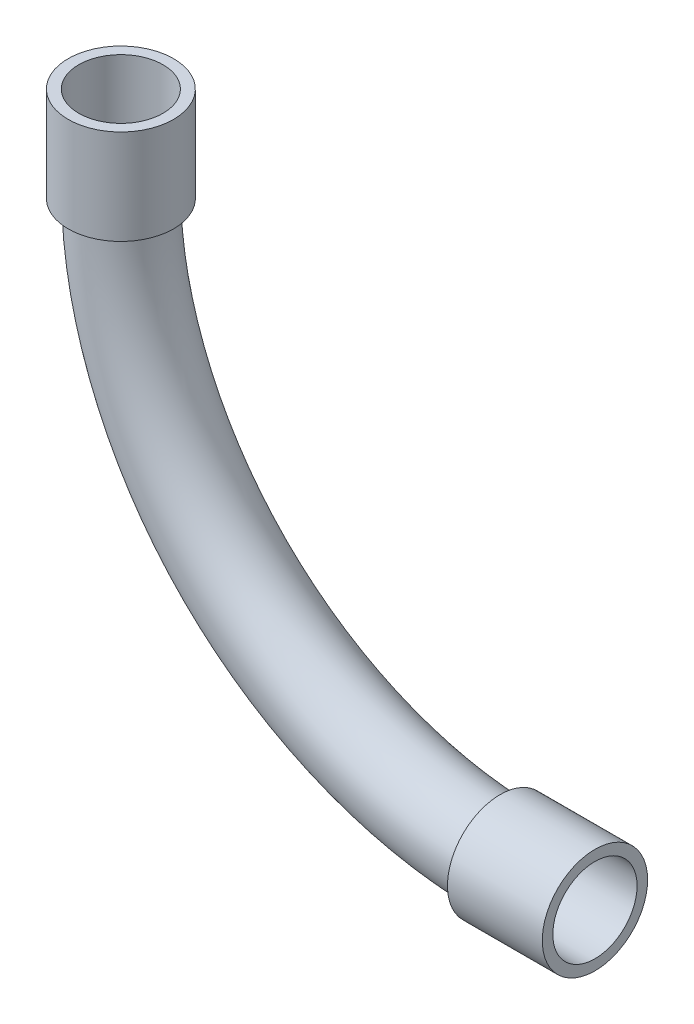
SolidWorks part; units mm, degrees
ref_plane "Front Plane" through (0, 0, 0) normal (0, 0, 1) x (1, 0, 0)
ref_plane "Top Plane" through (0, 0, 0) normal (0, 1, 0) x (1, 0, 0)
ref_plane "Right Plane" through (0, 0, 0) normal (1, 0, 0) x (0, 0, -1)
sketch "Sketch5" plane through (0, 0, 0) normal (0, 0, 1) x (1, 0, 0)
  line L0 (0, 0) -> (0, 74) construction
  line L1 (0, 0) -> (74, 0) construction
  arc A0 (74, 0) -> (0, 74) centre (74, 74) cw
  dimension "h1" = 74
ref_plane "Plane1" through (74, 0, 0) normal (1, 0, 0) x (0, 0, -1)
sketch "Sketch8" plane through (74, 0, 0) normal (1, 0, 0) x (0, 0, -1)
  circle A0 centre (0, 0) radius 6
  dimension "e1" = 12
ref_plane "Plane2" through (0, 74, 0) normal (0, 1, 0) x (1, 0, 0)
sketch "Sketch9" plane through (0, 74, 0) normal (0, 1, 0) x (1, 0, 0)
  circle A0 centre (0, 0) radius 6
  dimension "e2" = 12
sketch "Sketch10" plane through (0, 74, 0) normal (0, 1, 0) x (1, 0, 0)
  circle A0 centre (0, 0) radius 8
  dimension "c1" = 16
sketch "Sketch11" plane through (74, 0, 0) normal (1, 0, 0) x (0, 0, -1)
  circle A0 centre (0, 0) radius 8
  dimension "c2" = 16
sweep "Sweep-Thin1" add profiles "Sketch8" path "Sketch5" parameters "D1"=2
extrude "Extrude-Thin1" add sketch "Sketch11" along normal blind 16 and the other way blind 2 separate body thin
extrude "Extrude-Thin2" add sketch "Sketch10" along normal blind 16 and the other way blind 2 separate body thin
